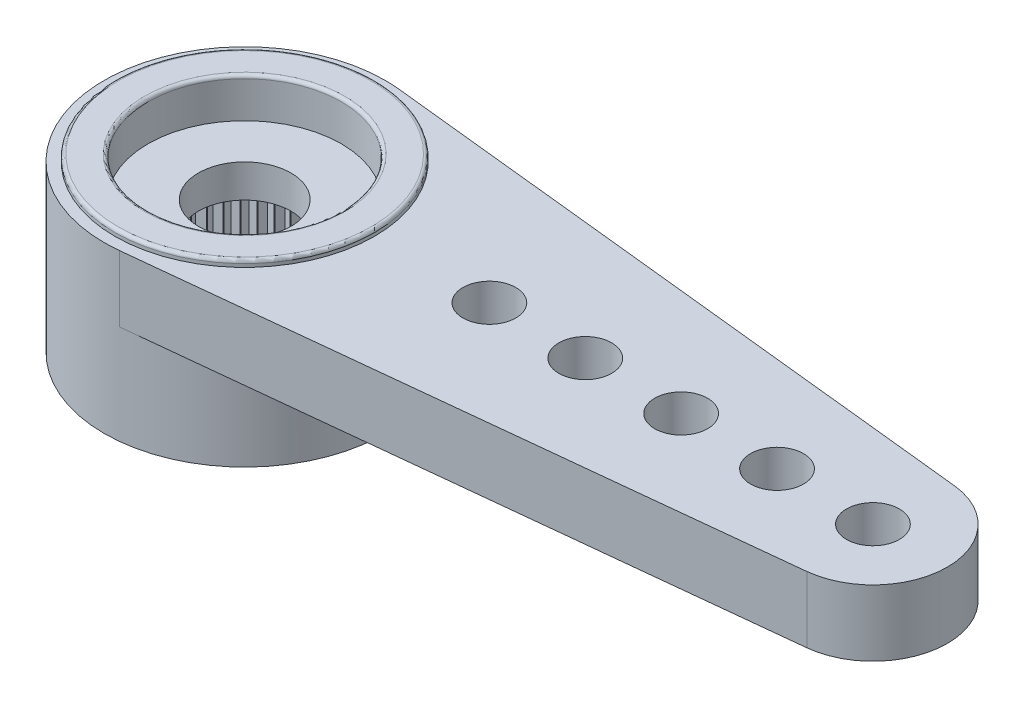
SolidWorks part; units mm, degrees
ref_plane "Front Plane" through (0, 0, 0) normal (0, 0, 1) x (1, 0, 0)
ref_plane "Top Plane" through (0, 0, 0) normal (0, 1, 0) x (1, 0, 0)
ref_plane "Right Plane" through (0, 0, 0) normal (1, 0, 0) x (0, 0, -1)
sketch "Sketch2" plane through (0, 0, 0) normal (0, 1, 0) x (1, 0, 0)
  line L0 (19.2368, 2.2375) -> (0.4474, 4.2264)
  line L1 (19.2368, -2.2375) -> (0.4474, -4.2264)
  arc A0 (0.4474, 4.2264) -> (0.4474, -4.2264) centre (0, 0) ccw
  arc A1 (19.2368, 2.2375) -> (19.2368, -2.2375) centre (19, 0) cw
  dimension "D1" = 2.25
  dimension "D2" = 4.25
  dimension "D3" = 19
extrude "Boss-Extrude1" add sketch "Sketch2" along normal blind 2
sketch "Sketch3" plane through (0, 2, 0) normal (0, 1, 0) x (1, 0, 0)
  circle A0 centre (0, 0) radius 3.925
  circle A1 centre (0, 0) radius 2.925
  dimension "D1" = 5.85
  dimension "D2" = 7.85
extrude "Boss-Extrude2" add sketch "Sketch3" along normal blind 0.2
sketch "Sketch4" plane through (0, 0, 0) normal (0, -1, 0) x (1, 0, 0)
  circle A0 centre (0, 0) radius 4.25
extrude "Boss-Extrude3" add sketch "Sketch4" along normal blind 3
sketch "Sketch5" plane through (0, -3, 0) normal (0, -1, 0) x (1, 0, 0)
  circle A0 centre (0, 0) radius 2.9
  dimension "D1" = 5.8
extrude "Cut-Extrude1" cut sketch "Sketch5" against normal blind 3
sketch "Sketch6" plane through (0, 2, 0) normal (0, 1, 0) x (1, 0, 0)
  circle A0 centre (0, 0) radius 1.4
  dimension "D1" = 2.8
extrude "Cut-Extrude2" cut sketch "Sketch6" against normal up to next
sketch "Sketch7" plane through (0, 2, 0) normal (0, 1, 0) x (1, 0, 0)
  circle A0 centre (0, 0) radius 2.925
extrude "Cut-Extrude3" cut sketch "Sketch7" against normal blind 1
sketch "Sketch8" plane through (0, 2, 0) normal (0, 1, 0) x (1, 0, 0)
  line L0 (0, 0) -> (19, 0) construction
  circle A0 centre (19, 0) radius 0.8
  dimension "D1" = 1.6
extrude "Cut-Extrude4" cut sketch "Sketch8" against normal up to next
pattern_linear "LPattern1" count 5 spacing 2.9 along (-1, 0, 0) of "Cut-Extrude4"
fillet "Fillet1" radius 0.1 2 edges at (0, 2.2, 2.925) (0, 2.2, 3.925)
sketch "Sketch9" plane through (0, -3, 0) normal (0, -1, 0) x (1, 0, 0)
  line L3 (0, 3.1) -> (-0.25, 2.8)
  line L4 (-0.25, 2.8) -> (0.25, 2.8)
  line L5 (0.25, 2.8) -> (0, 3.1)
  point P2 (0, 2.8)
  dimension "D1" = 0.5
  dimension "D2" = 0.3
  dimension "D3" = 2.8
extrude "Cut-Extrude5" cut sketch "Sketch9" against normal up to surface (3 mm away) up to face at (0, 0, -1.4)
pattern_circular "CirPattern1" count 50 over 360 about axis through (0, 0, 0) along (0, 1, 0) of "Cut-Extrude5"
